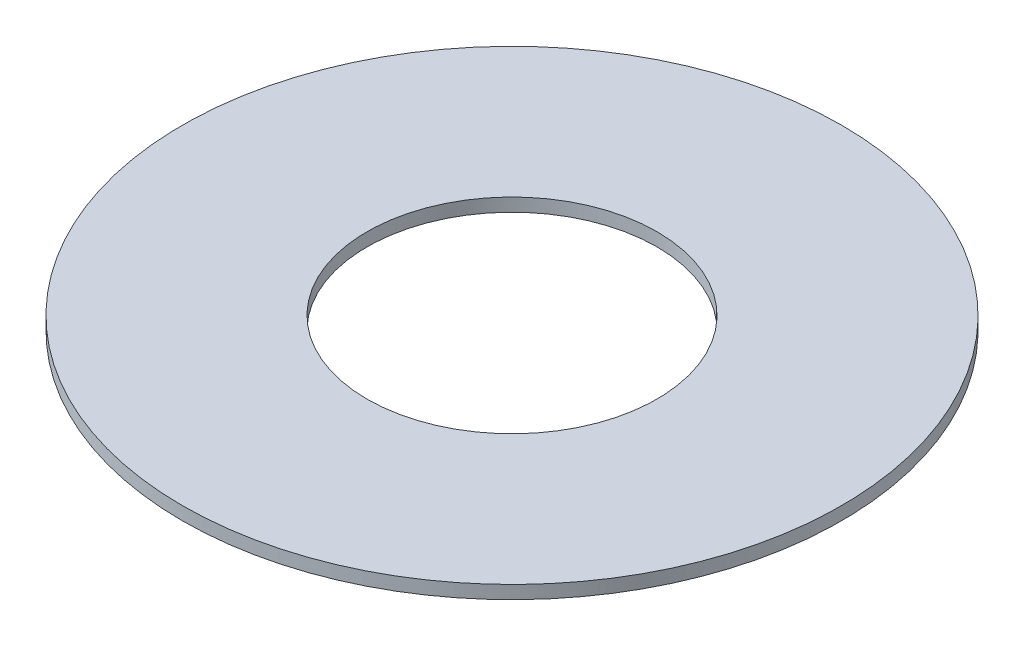
SolidWorks part; units mm, degrees
ref_plane "Plan de face" through (0, 0, 0) normal (0, 0, 1) x (1, 0, 0)
ref_plane "Plan de dessus" through (0, 0, 0) normal (0, 1, 0) x (1, 0, 0)
ref_plane "Plan de droite" through (0, 0, 0) normal (1, 0, 0) x (0, 0, -1)
sketch "Esquisse1" plane through (0, 0, 0) normal (0, 1, 0) x (1, 0, 0)
  circle A0 centre (0, 0) radius 55
  circle A1 centre (0, 0) radius 125
  dimension "D1" = 110
  dimension "D2" = 250
extrude "Boss.-Extru.1" add sketch "Esquisse1" along normal blind 5
